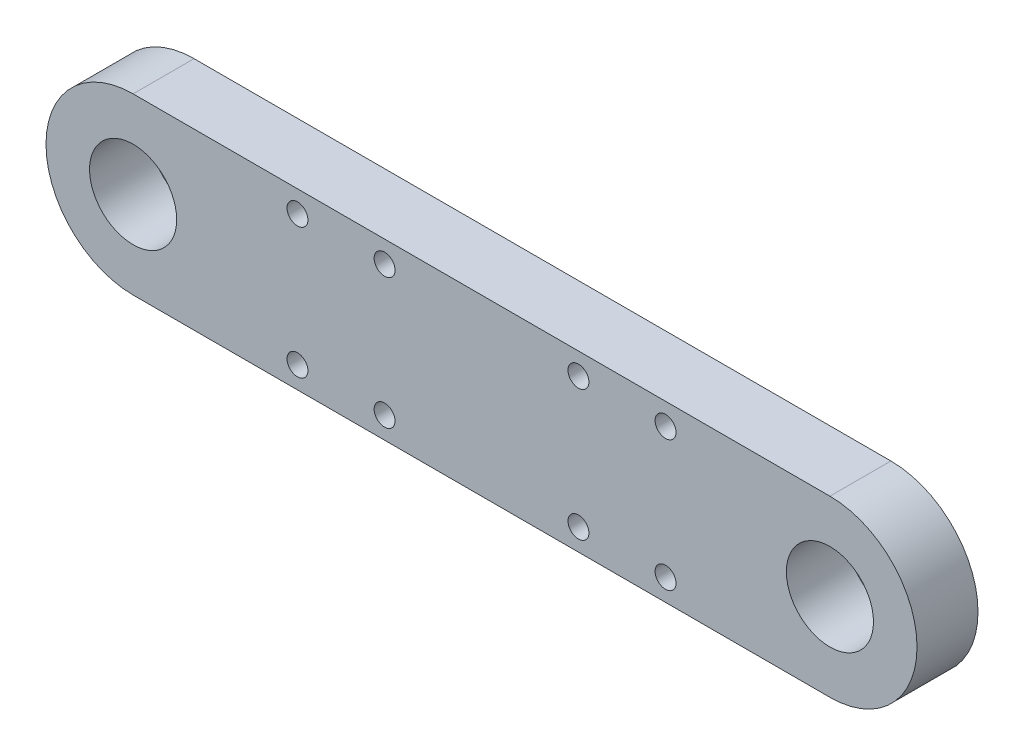
SolidWorks part; units mm, degrees
ref_plane "前视基准面" through (0, 0, 0) normal (0, 0, 1) x (1, 0, 0)
ref_plane "上视基准面" through (0, 0, 0) normal (0, 1, 0) x (1, 0, 0)
ref_plane "右视基准面" through (0, 0, 0) normal (1, 0, 0) x (0, 0, -1)
other "Configuration Table"
sketch "草图1" plane through (0, 0, 0) normal (0, 0, 1) x (1, 0, 0)
  line L0 (0, 10) -> (80, 10)
  line L1 (0, -10) -> (80, -10)
  circle A0 centre (0, 0) radius 10
  arc A1 (80, -10) -> (80, 10) centre (80, 0) ccw
  circle A2 centre (0, 0) radius 5
  dimension "D1" = 20
  dimension "D2" = 80
  dimension "D3" = 10
extrude "凸台-拉伸1" add sketch "草图1" along normal blind 7 contours A0 A2 | L1 A1 L0 A0
sketch "草图2" plane through (0, 0, 0) normal (0, 0, -1) x (-1, 0, 0)
  circle A0 centre (-51.129, -7.5) radius 1.2 construction
  circle A1 centre (-51.129, -7.5) radius 1.2
  circle A2 centre (-61.129, -7.5) radius 1.2 construction
  circle A3 centre (-61.129, -7.5) radius 1.2
  circle A4 centre (-61.129, 7.5) radius 1.2 construction
  circle A5 centre (-61.129, 7.5) radius 1.2
  circle A6 centre (-51.129, 7.5) radius 1.2 construction
  circle A7 centre (-51.129, 7.5) radius 1.2
extrude "切除-拉伸1" cut sketch "草图2" against normal blind 10
sketch "草图3" plane through (0, 0, 7) normal (0, 0, 1) x (1, 0, 0)
  line L0 (40, 10) -> (40, -10) construction
  line L1 (0, 10) -> (80, 10) construction
  line L2 (0, -10) -> (80, -10) construction
  circle A0 centre (0, 0) radius 5 construction
  circle A1 centre (0, 0) radius 5
  circle A2 centre (80, 0) radius 5
extrude "切除-拉伸2" cut sketch "草图3" against normal blind 10
sketch "草图4" plane through (0, 0, 7) normal (0, 0, 1) x (1, 0, 0)
  line L0 (40, 10) -> (40, -10) construction
  line L1 (0, 10) -> (80, 10) construction
  line L2 (0, -10) -> (80, -10) construction
  circle A0 centre (61.129, 7.5) radius 1.2 construction
  circle A1 centre (61.129, -7.5) radius 1.2 construction
  circle A2 centre (51.129, -7.5) radius 1.2 construction
  circle A3 centre (51.129, 7.5) radius 1.2 construction
  circle A4 centre (61.129, 7.5) radius 1.2
  circle A5 centre (61.129, -7.5) radius 1.2
  circle A6 centre (51.129, -7.5) radius 1.2
  circle A7 centre (51.129, 7.5) radius 1.2
  circle A8 centre (28.871, 7.5) radius 1.2
  circle A9 centre (28.871, -7.5) radius 1.2
  circle A10 centre (18.871, -7.5) radius 1.2
  circle A11 centre (18.871, 7.5) radius 1.2
extrude "切除-拉伸3" cut sketch "草图4" against normal blind 10
